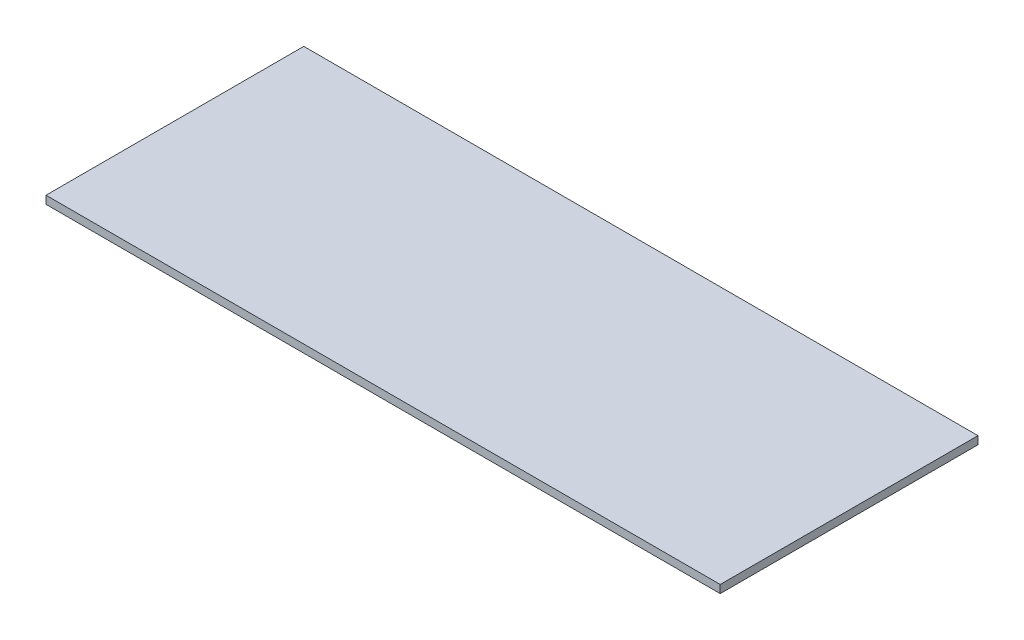
SolidWorks part; units mm, degrees
ref_plane "Front Plane" through (0, 0, 0) normal (0, 0, 1) x (1, 0, 0)
ref_plane "Top Plane" through (0, 0, 0) normal (0, 1, 0) x (1, 0, 0)
ref_plane "Right Plane" through (0, 0, 0) normal (1, 0, 0) x (0, 0, -1)
ref_plane "Plane1" through (0, 71.8, 0) normal (0, 1, 0) x (1, 0, 0)
sketch "Sketch1" plane through (0, 71.8, 0) normal (0, 1, 0) x (1, 0, 0)
  line L0 (130, -280) -> (470, -280)
  line L1 (470, -280) -> (470, -410)
  line L2 (470, -410) -> (130, -410)
  line L3 (130, -410) -> (130, -280)
extrude "Boss-Extrude1" add sketch "Sketch1" along normal blind 4
